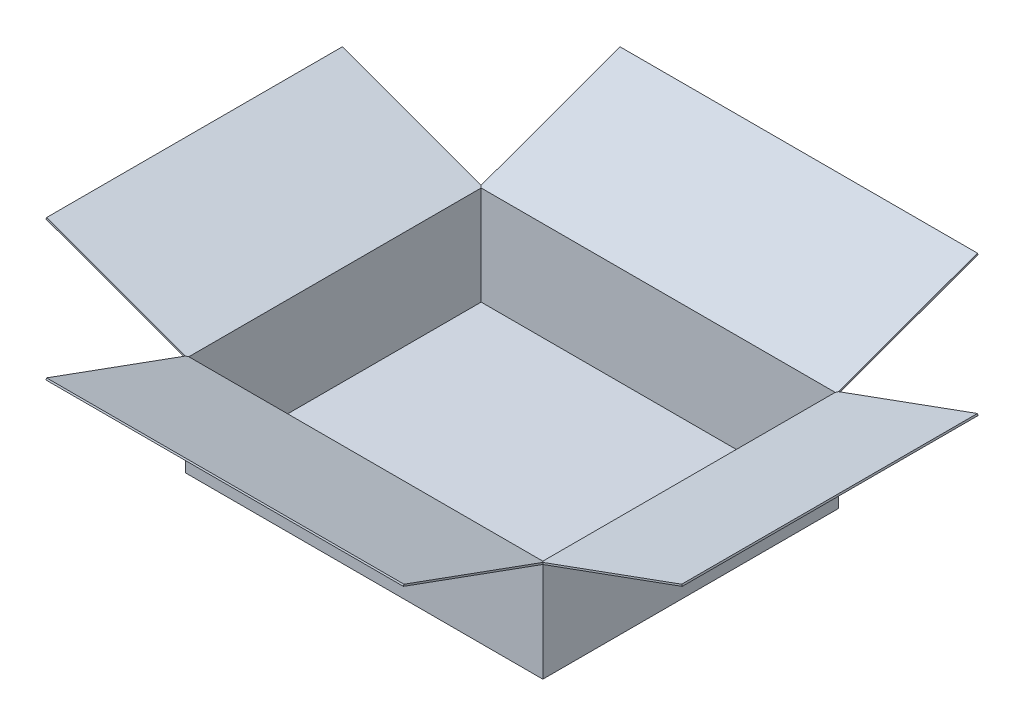
SolidWorks part; units mm, degrees
ref_plane "Front Plane" through (0, 0, 0) normal (0, 0, 1) x (1, 0, 0)
ref_plane "Top Plane" through (0, 0, 0) normal (0, 1, 0) x (1, 0, 0)
ref_plane "Right Plane" through (0, 0, 0) normal (1, 0, 0) x (0, 0, -1)
sketch "Sketch1" plane through (0, 0, 0) normal (0, 1, 0) x (1, 0, 0)
  line L1 (-211.5, -175) -> (211.5, -175)
  line L2 (-211.5, -175) -> (-211.5, 175)
  line L3 (-211.5, 175) -> (211.5, 175)
  line L4 (211.5, -175) -> (211.5, 175)
  line L5 (-211.5, -175) -> (211.5, 175) construction
  line L6 (-211.5, 175) -> (211.5, -175) construction
  point P0 (0, 0)
  dimension "D1" = 350
  dimension "D2" = 423
extrude "Boss-Extrude1" add sketch "Sketch1" along normal blind 119
shell "Shell1" thickness 2
sketch "Sketch2" plane through (211.5, 0, 0) normal (1, 0, 0) x (0, 0, -1)
  line L0 (-173, 119) -> (-339.3256, 179.5376)
  line L1 (-339.3256, 179.5376) -> (-340.0096, 177.6582)
  line L2 (-340.0096, 177.6582) -> (-173.684, 117.1206)
  line L3 (-173.684, 117.1206) -> (-173, 119)
  line L4 (-175, 119) -> (-175, 0) construction
  dimension "D1" = 177
  dimension "D2" = 2
  dimension "D3" = 110
extrude "Boss-Extrude2" add sketch "Sketch2" against normal up to surface (423 mm away) up to face at (-211.5, 59.5, 0)
sketch "Sketch4" plane through (0, 0, -175) normal (0, 0, -1) x (-1, 0, 0)
  line L0 (-209.5, 119) -> (-375.8256, 179.5376)
  line L1 (-375.8256, 179.5376) -> (-376.5096, 177.6582)
  line L2 (-376.5096, 177.6582) -> (-210.184, 117.1206)
  line L3 (-210.184, 117.1206) -> (-209.5, 119)
  line L4 (-211.5, 119) -> (-211.5, 0) construction
  dimension "D1" = 2
  dimension "D2" = 110
  dimension "D3" = 177
extrude "Boss-Extrude3" add sketch "Sketch4" against normal up to surface (350 mm away) up to face at (0, 58.7998, 175)
mirror "Mirror1" about plane through (0, 0, 0) normal (0, 0, 1) of "Boss-Extrude2"
mirror "Mirror2" about plane through (0, 0, 0) normal (1, 0, 0) of "Boss-Extrude3"
